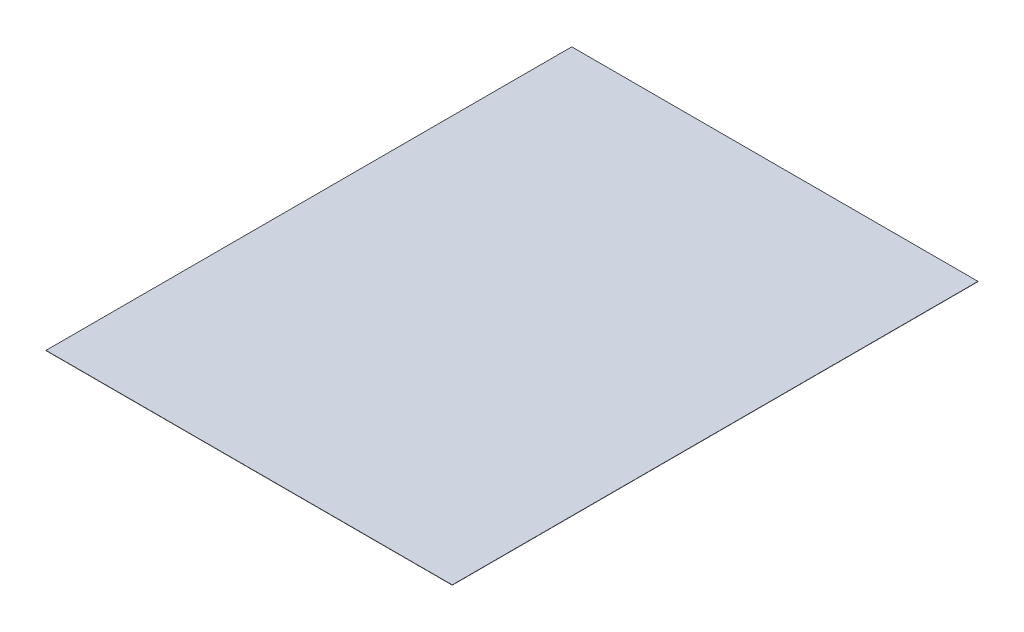
SolidWorks part; units mm, degrees
material "Polyurethane Foam Rigid"
ref_plane "Front Plane" through (0, 0, 0) normal (0, 0, 1) x (1, 0, 0)
ref_plane "Top Plane" through (0, 0, 0) normal (0, 1, 0) x (1, 0, 0)
ref_plane "Right Plane" through (0, 0, 0) normal (1, 0, 0) x (0, 0, -1)
sketch "Sketch1" plane through (0, 0, 0) normal (0, 1, 0) x (1, 0, 0)
  line L1 (0, 0) -> (215.9, 0)
  line L2 (0, 0) -> (0, 279.4)
  line L3 (0, 279.4) -> (215.9, 279.4)
  line L4 (215.9, 0) -> (215.9, 279.4)
  dimension "D1" = 215.9
  dimension "D2" = 279.4
extrude "Boss-Extrude1" add sketch "Sketch1" along normal blind 0.127
